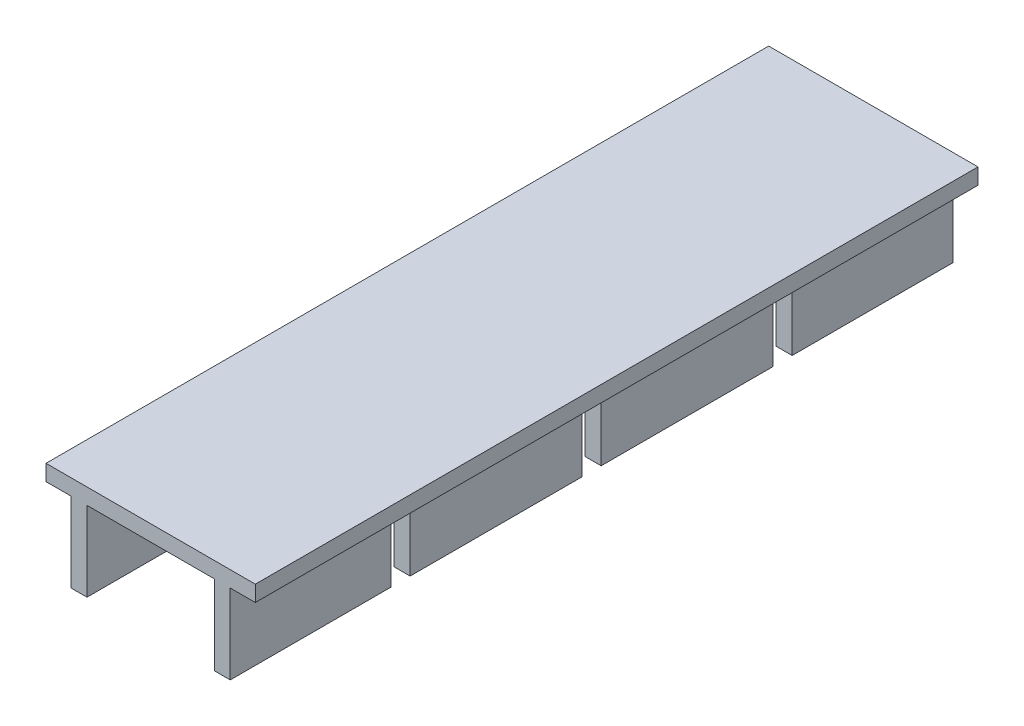
SolidWorks part; units mm, degrees
ref_plane "Front Plane" through (0, 0, 0) normal (0, 0, 1) x (1, 0, 0)
ref_plane "Top Plane" through (0, 0, 0) normal (0, 1, 0) x (1, 0, 0)
ref_plane "Right Plane" through (0, 0, 0) normal (1, 0, 0) x (0, 0, -1)
sketch "Sketch1" plane through (0, 0, 0) normal (0, 0, 1) x (1, 0, 0)
  line L0 (57.15, 0) -> (57.15, 31.75)
  line L1 (0, 0) -> (6.35, 0)
  line L2 (0, 0) -> (0, 31.75)
  line L3 (0, 38.1) -> (63.5, 38.1)
  line L4 (63.5, 0) -> (63.5, 9.525)
  line L5 (6.35, 31.75) -> (57.15, 31.75)
  line L6 (6.35, 0) -> (6.35, 31.75)
  line L7 (57.15, 0) -> (63.5, 0)
  line L14 (63.5, 38.1) -> (73.5, 38.1)
  line L15 (0, 0) -> (0, 38.1) construction
  line L16 (63.5, 9.525) -> (63.5, 31.75)
  line L22 (63.5, 31.75) -> (73.5, 31.75)
  line L23 (63.5, 0) -> (63.5, 38.1) construction
  line L24 (73.5, 38.1) -> (73.5, 31.75)
  line L25 (0, 38.1) -> (-10, 38.1)
  line L27 (0, 31.75) -> (-10, 31.75)
  line L28 (-10, 38.1) -> (-10, 31.75)
  dimension "D1" = 63.5
  dimension "D2" = 38.1
  dimension "D4" = 6.35
  dimension "D5" = 6.35
  dimension "D6" = 83.5
  dimension "D3" = 6.35
extrude "Boss-Extrude1" add sketch "Sketch1" along normal blind 288.29
sketch "Sketch2" plane through (0, 0, 0) normal (-1, 0, 0) x (0, 0, 1)
  line L1 (50.8, 0) -> (0, 0)
  line L2 (50.8, 0) -> (50.8, 12.7)
  line L3 (50.8, 12.7) -> (0, 12.7)
  line L4 (0, 0) -> (0, 12.7)
  dimension "D1" = 12.7
  dimension "D2" = 50.8
extrude "Cut-Extrude1" [suppressed] cut sketch "Sketch2" against normal up to surface (63.5 mm away)
sketch "Sketch3" plane through (0, 38.1, 0) normal (0, 1, 0) x (1, 0, 0)
  line L0 (31.75, 0) -> (31.75, 25.4) construction
  line L1 (73.5, 0) -> (-10, 0) construction
  line L2 (-10, 0) -> (73.5, 0)
  arc A0 (-10, 0) -> (31.75, 25.4) centre (-12.2734, 50.7491) ccw
  arc A1 (31.75, 25.4) -> (73.5, 0) centre (75.7734, 50.7491) ccw
  dimension "D2" = 50.8
  dimension "D3" = 50.8
  dimension "D1" = 25.4
extrude "Boss-Extrude2" [suppressed] add sketch "Sketch3" against normal up to surface (6.35 mm away) separate body
sketch "Sketch4" plane through (63.5, 0, 0) normal (1, 0, 0) x (0, 0, -1)
  line L0 (-288.29, 0) -> (0, 0) construction
  line L1 (-224.155, 0) -> (-216.535, 0)
  line L2 (-224.155, 0) -> (-224.155, 23.8125)
  line L3 (-224.155, 23.8125) -> (-216.535, 23.8125)
  line L4 (-216.535, 0) -> (-216.535, 23.8125)
  line L5 (-288.29, 38.1) -> (0, 38.1) construction
  line L6 (-288.29, 0) -> (-288.29, 31.75) construction
  dimension "D1" = 7.62
  dimension "D2" = 14.2875
  dimension "D3" = 64.135
extrude "Cut-Extrude2" cut sketch "Sketch4" against normal up to surface (63.5 mm away) up to face at (0, 15.875, 144.145)
pattern_linear "LPattern1" count 3 spacing 76.2 along (0, 0, -1) of "Cut-Extrude2"
sketch "Sketch5" plane through (63.5, 0, 0) normal (1, 0, 0) x (0, 0, -1)
  line B0 (-216.535, 0) -> (-147.955, 0)
  line B1 (-147.955, 0) -> (-147.955, 23.8125)
  line B2 (-147.955, 23.8125) -> (-140.335, 23.8125)
  line B3 (-140.335, 23.8125) -> (-140.335, 0)
  line B4 (-140.335, 0) -> (-71.755, 0)
  line B5 (-71.755, 0) -> (-71.755, 23.8125)
  line B6 (-71.755, 23.8125) -> (-64.135, 23.8125)
  line B7 (-64.135, 23.8125) -> (-64.135, 0)
  line B8 (-64.135, 0) -> (0, 0)
  line B9 (0, 0) -> (0, 31.75)
  line B10 (0, 31.75) -> (-288.29, 31.75)
  line B11 (-288.29, 31.75) -> (-288.29, 0)
  line B12 (-288.29, 0) -> (-224.155, 0)
  line B13 (-224.155, 0) -> (-224.155, 23.8125)
  line B14 (-224.155, 23.8125) -> (-216.535, 23.8125)
  line B15 (-216.535, 23.8125) -> (-216.535, 0)
sketch_block_instance "Block1-1"
sketch_block "Block1"
